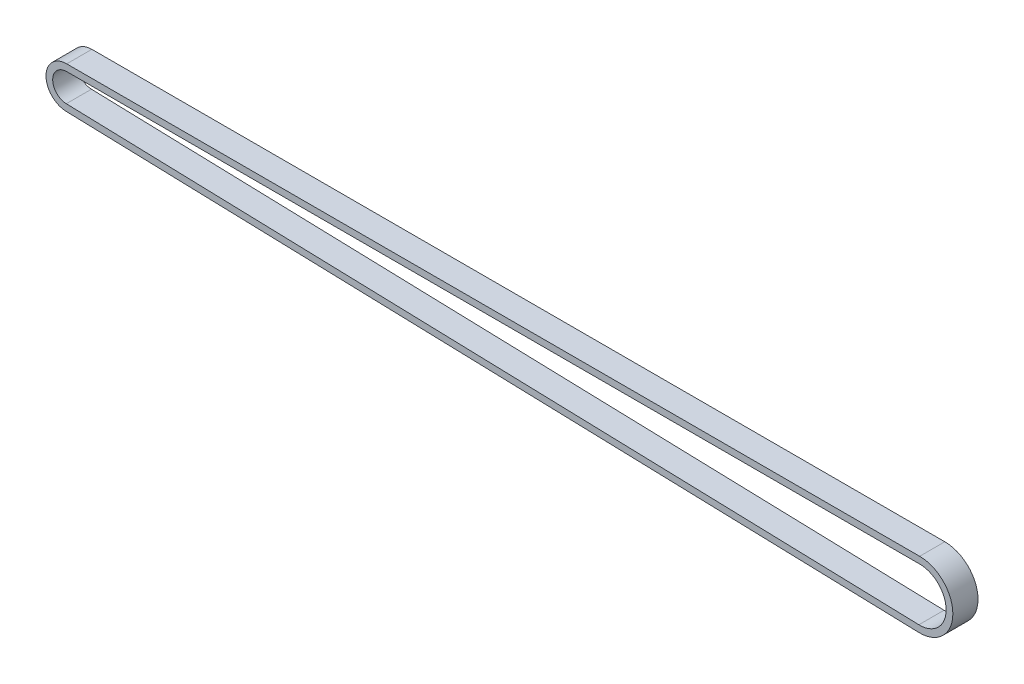
SolidWorks part; units mm, degrees
ref_plane "Front Plane" through (0, 0, 0) normal (0, 0, 1) x (1, 0, 0)
ref_plane "Top Plane" through (0, 0, 0) normal (0, 1, 0) x (1, 0, 0)
ref_plane "Right Plane" through (0, 0, 0) normal (1, 0, 0) x (0, 0, -1)
sketch "Sketch1" plane through (0, 0, 0) normal (0, 0, 1) x (1, 0, 0)
  line L0 (0, 7.8486) -> (322.9654, 7.8486)
  line L1 (0, 0) -> (322.9654, -4.7244) construction
  line L2 (-0.2296, -7.8452) -> (322.5977, -17.292)
  line L3 (0, 5.3086) -> (322.9654, 5.3086)
  line L4 (-0.1553, -5.3063) -> (322.672, -14.7531)
  arc A0 (0, 7.8486) -> (-0.2296, -7.8452) centre (0, 0) ccw
  arc A1 (322.5977, -17.292) -> (322.9654, 7.8486) centre (322.9654, -4.7244) ccw
  arc A2 (322.672, -14.7531) -> (322.9654, 5.3086) centre (322.9654, -4.7244) ccw
  arc A3 (0, 5.3086) -> (-0.1553, -5.3063) centre (0, 0) ccw
  dimension "D2" = 15.6972
  dimension "D3" = 25.146
  dimension "D1" = 323
  dimension "D4" = 2.54
extrude "Boss-Extrude1" add sketch "Sketch1" along normal blind 9.525
